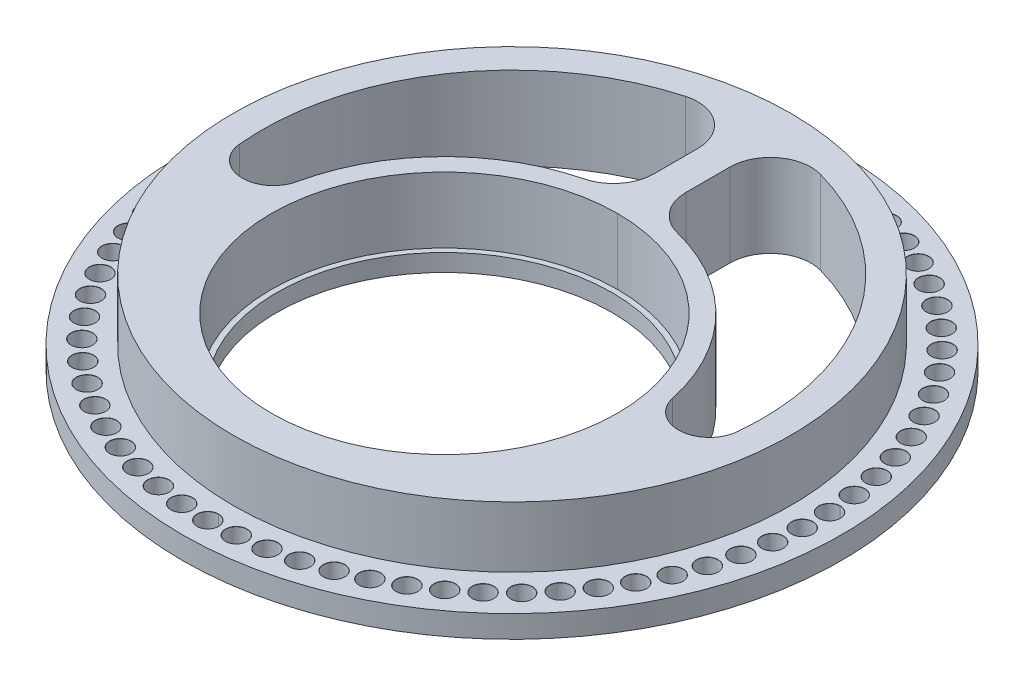
SolidWorks part; units mm, degrees
material "6061-T6 (SS)"
ref_plane "X-Y Datum" through (0, 0, 0) normal (0, 0, 1) x (1, 0, 0)
ref_plane "X-Z Datum" through (0, 0, 0) normal (0, 1, 0) x (1, 0, 0)
ref_plane "Y-Z Datum" through (0, 0, 0) normal (1, 0, 0) x (0, 0, -1)
sketch "Sketch1" plane through (0, 0, 0) normal (0, 1, 0) x (1, 0, 0)
  line L0 (0, 0) -> (0, -12.7) construction
  line L1 (0, -43.0151) -> (0, 43.0151) construction
  line L2 (0, 52.3875) -> (0, 61.9125) construction
  circle A0 centre (0, -12.7) radius 30.988
  circle A1 centre (0, 0) radius 52.3875 construction
  circle A2 centre (0, 0) radius 61.9125
  circle A3 centre (0, 0) radius 57.15 construction
  point P12 (0, 57.15)
  dimension "D2" = 61.976
  dimension "D3" = 104.775
  dimension "D4" = 123.825
  dimension "D5" = 114.3
  dimension "D1" = 12.7
extrude "Slotted-Body Extrude" add sketch "Sketch1" along normal blind 4.191
sketch "Sketch5" plane through (0, 4.191, 0) normal (0, 1, 0) x (1, 0, 0)
  circle A0 centre (0, 0) radius 52.3875 construction
  circle A1 centre (0, 0) radius 52.3875
extrude "Boss-Extrude3" add sketch "Sketch5" along normal blind 11.43
sketch "Sketch6" plane through (0, 0, 0) normal (0, -1, 0) x (1, 0, 0)
  line L0 (0, -79.2756) -> (0, 0) construction
  line L2 (3.014, -37.9067) -> (3.014, -29.6741)
  line L4 (-3.014, -37.9067) -> (-3.014, -29.6741)
  circle A0 centre (0, 12.7) radius 30.988 construction
  circle A1 centre (0, 12.7) radius 30.988 construction
  circle A2 centre (0, 12.7) radius 32.512
  arc A9 (-35.2562, 5.0907) -> (-8.7792, -22.2832) centre (0, 12.7) ccw
  arc A10 (-46.783, 4.406) -> (-12.6921, -45.2435) centre (0, 0) ccw
  arc A11 (-46.783, 4.406) -> (-35.2562, 5.0907) centre (-40.9667, 3.8583) cw
  arc A19 (-3.014, -29.6741) -> (-8.7792, -22.2832) centre (-10.634, -29.6741) ccw
  arc A20 (-3.014, -37.9067) -> (-12.6921, -45.2435) centre (-10.634, -37.9067) cw
  circle A21 centre (0, 0) radius 61.9125 construction
  arc A27 (46.783, 4.406) -> (35.2562, 5.0907) centre (40.9667, 3.8583) ccw
  arc A28 (46.783, 4.406) -> (12.6921, -45.2435) centre (0, 0) cw
  arc A29 (3.014, -37.9067) -> (12.6921, -45.2435) centre (10.634, -37.9067) ccw
  arc A30 (3.014, -29.6741) -> (8.7792, -22.2832) centre (10.634, -29.6741) cw
  arc A31 (35.2562, 5.0907) -> (8.7792, -22.2832) centre (0, 12.7) cw
  point P30 (0, 0)
  point P31 (-3.014, -23.2419)
  point P32 (0, 0)
  point P36 (-3.014, -46.8932)
  dimension "D1" = 65.024
  dimension "D2" = 7.62
  dimension "D3" = 5.842
  dimension "D4" = 46.99
  dimension "D5" = 7.62
  dimension "D6" = 36.068
  dimension "D8" = 8.2326
extrude "Cut-Extrude5" cut sketch "Sketch6" against normal through all
sketch "Sketch8" plane through (0, 0, 0) normal (0, -1, 0) x (1, 0, 0)
  circle A0 centre (0, 12.7) radius 32.512 construction
  circle A1 centre (0, 12.7) radius 32.512
  circle A2 centre (0, 12.7) radius 31.496
  dimension "D1" = 62.992
extrude "Boss-Extrude4" add sketch "Sketch8" against normal blind 3.255 separate body
hole_wizard "Ø4.0mm Dowel Hole2" positions "Sketch9" profile "Sketch10" hole size "Ø4.0" standard "ANSI Metric" end condition through all
sketch "Sketch9" plane through (0, 4.191, 0) normal (0, 1, 0) x (1, 0, 0)
  point P0 (0, 57.15)
sketch "Sketch10" plane through (0, 4.191, -57.15) normal (1, 0, 0) x (0, 0, 1)
  line L0 (0, 0) -> (0, 4.191)
  line L1 (0, 4.191) -> (2, 4.191)
  line L2 (2, 4.191) -> (2, 0.025)
  line L3 (2, 0.025) -> (2.025, 0)
  line L5 (2.025, 0) -> (0, 0)
  line L6 (-2, 0.025) -> (-2.025, 0) construction
  line L11 (0, -6.35) -> (0, 107.95) construction
  dimension "Thru Hole Dia." = 4
  dimension "Thru Hole Depth" = 4.191
  dimension "Near C'Sink Dia." = 4.05
  dimension "Near C'Sink Angle" = 90
pattern_circular "CirPattern1" count 70 over 360 about axis through (0, 0, 0) along (0, 1, 0) of "Ø4.0mm Dowel Hole2"
ref_point "Point1"
ref_plane "Plane1" through (0, 0, 0) normal (1, 0, 0) x (0, 0, -1)
split line "Split Line1"
ref_point "Point2"
ref_point "Point3"
ref_point "Point4"
ref_point "Point5"
split line "Split Line2"
split line "Split Line3"
ref_plane "Plane2" through (-57.0925, 0, 0) normal (-1, 0, 0) x (0, 0, 1)
ref_plane "Plane3" through (57.0925, 0, 0) normal (-1, 0, 0) x (0, 0, 1)
split line "Split Line4"
split line "Split Line5"
